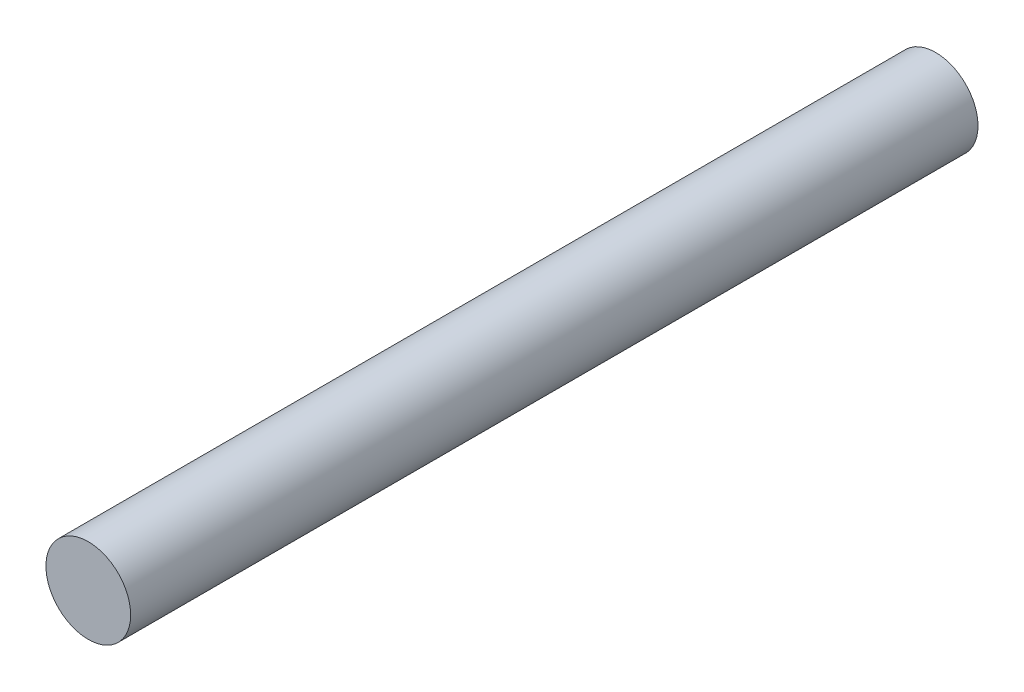
SolidWorks part; units mm, degrees
ref_plane "Plano frontal" through (0, 0, 0) normal (0, 0, 1) x (1, 0, 0)
ref_plane "Plano superior" through (0, 0, 0) normal (0, 1, 0) x (1, 0, 0)
ref_plane "Plano direito" through (0, 0, 0) normal (1, 0, 0) x (0, 0, -1)
sketch "Esboço1" plane through (0, 0, 0) normal (0, 0, 1) x (1, 0, 0)
  circle A0 centre (0, 0) radius 3
  dimension "D1" = 6
extrude "Ressalto-extrusão1" add sketch "Esboço1" along normal blind 60
cosmetic thread "Representação de rosca2" parameters "D1"=23, "D2"=5.16
hole_wizard "Furo roscado de M41" positions "Esboço2" profile "Esboço3" tap size "M4" standard "DIN"
sketch "Esboço2" plane through (0, 0, 0) normal (0, 0, -1) x (-1, 0, 0)
  point P1 (0, 0)
sketch "Esboço3" plane through (0, 0, 0) normal (1, 0, 0) x (0, 1, 0)
  line L0 (0, 0) -> (0, 20.9914)
  line L1 (0, 20.9914) -> (1.65, 20)
  line L2 (1.65, 20) -> (1.65, 0.375)
  line L3 (1.65, 0.375) -> (2.025, 0)
  line L5 (2.025, 0) -> (0, 0)
  line L6 (-1.65, 0.375) -> (-2.025, 0) construction
  line L10 (0, 20.9914) -> (-1.65, 20) construction
  line L11 (0, -6.35) -> (0, 107.95) construction
  dimension "Tap Drill Dia." = 3.3
  dimension "Tap Drill Depth" = 20
  dimension "Near C'Sink Dia." = 4.05
  dimension "Near C'Sink Angle" = 90
  dimension "Drill Angle" = 118
cosmetic thread "Rosca de furo1"
